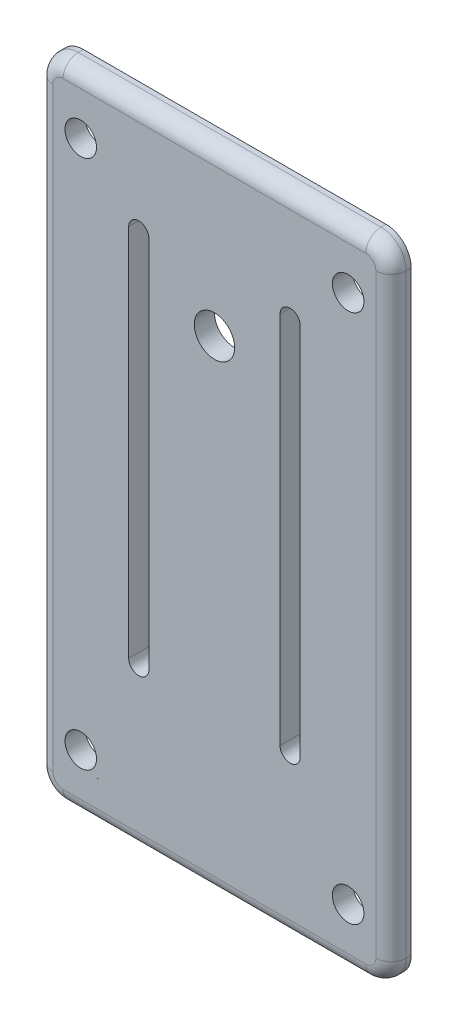
SolidWorks part; units mm, degrees
ref_plane "Front Plane" through (0, 0, 0) normal (0, 0, 1) x (1, 0, 0)
ref_plane "Top Plane" through (0, 0, 0) normal (0, 1, 0) x (1, 0, 0)
ref_plane "Right Plane" through (0, 0, 0) normal (1, 0, 0) x (0, 0, -1)
sketch "Sketch1" plane through (0, 0, 0) normal (0, 0, 1) x (1, 0, 0)
  line L1 (0, 32) -> (0, -32) construction
  line L2 (16.455, 32) -> (-16.455, 32) construction
  line L3 (-16.455, -32) -> (16.455, -32) construction
  line L4 (17.455, 31) -> (17.455, -31) construction
  line L5 (17.455, 0) -> (-17.455, 0) construction
  line L6 (-17.455, 31) -> (-17.455, -31) construction
  line L7 (17.7124, 32) -> (16.455, 32) construction
  line L8 (-15, -32) -> (15, -32)
  line L9 (-17.5, -29.5) -> (-17.5, 29.5)
  line L10 (-15, 32) -> (15, 32)
  line L11 (17.5, -29.5) -> (17.5, 29.5)
  line L12 (0, 32) -> (0, -32) construction
  line L13 (-17.5, 0) -> (17.5, 0) construction
  arc A0 (-15, -32) -> (-17.5, -29.5) centre (-15, -29.5) cw
  arc A1 (15, -32) -> (17.5, -29.5) centre (15, -29.5) ccw
  arc A2 (15, 32) -> (17.5, 29.5) centre (15, 29.5) cw
  arc A3 (-17.5, 29.5) -> (-15, 32) centre (-15, 29.5) cw
  circle A4 centre (-11.5563, -27.8796) radius 0.0197
  circle A5 centre (-13.25, -26.25) radius 1.5625
  circle A6 centre (-13.25, 26.25) radius 1.5625
  circle A7 centre (-13.25, -26.25) radius 2.37 construction
  circle A8 centre (13.25, -26.25) radius 1.5625
  circle A9 centre (13.25, 26.25) radius 1.5625
  point P12 (0, 0)
  point P25 (17.5, 32)
  point P32 (0, 0)
  dimension "D3" = 2.5
  dimension "D4" = 0.0393
  dimension "D5" = 3.125
  dimension "D1" = 35
  dimension "D2" = 64
  dimension "D6" = 11.5563
  dimension "D7" = 27.8796
extrude "Boss-Extrude1" add sketch "Sketch1" along normal blind 2
sketch "Sketch2" plane through (0, 0, 2) normal (0, 0, 1) x (1, 0, 0)
  line L0 (-13.6273, 22.1478) -> (-13.6273, -16.8522) construction
  line L1 (-11.75, 22.1478) -> (-15.5046, 22.1478) construction
  line L2 (-15.5046, -16.8522) -> (-11.75, -16.8522) construction
  line L4 (0, 2.52) -> (-13.6273, 2.52) construction
  line L6 (-7.5, -16) -> (-7.5, 21.04) construction
  line L9 (0, -16.85) -> (0, 21.89) construction
  line L12 (-8.5, -16) -> (-8.5, 21.04)
  line L15 (-6.5, -16) -> (-6.5, 21.04)
  line L16 (7.5, -16) -> (7.5, 21.04) construction
  line L17 (8.5, -16) -> (8.5, 21.04)
  line L18 (6.5, -16) -> (6.5, 21.04)
  line L19 (17.5, -29.5) -> (17.5, 29.5) construction
  line L20 (-15, -32) -> (15, -32) construction
  line L21 (-13.6273, 2.6478) -> (0, 2.6478) construction
  arc A4 (-8.5, -16) -> (-6.5, -16) centre (-7.5, -16) ccw
  arc A5 (-6.5, 21.04) -> (-8.5, 21.04) centre (-7.5, 21.04) ccw
  arc A6 (8.5, -16) -> (6.5, -16) centre (7.5, -16) cw
  arc A7 (6.5, 21.04) -> (8.5, 21.04) centre (7.5, 21.04) cw
  point P11 (7.5, 2.52)
  point P14 (-7.5, 2.52)
  dimension "D3" = 17.5
  dimension "D4" = 16
  dimension "D2" = 10
  dimension "D1" = 2
  dimension "D5" = 34.52
fillet "Fillet1" radius 1.5 8 edges at (-16.7678, -31.2678, 2) (0, -32, 2) (16.7678, -31.2678, 2) (16.7678, 31.2678, 2) (17.5, 0, 2) (-16.7678, 31.2678, 2) (-17.5, 0, 2) (0, 32, 2)
sketch "Sketch3" plane through (0, 0, 2) normal (0, 0, 1) x (1, 0, 0)
  line L0 (16, -29.5) -> (16, 29.5) construction
  line L6 (-8.88, 26.4) -> (8.88, 26.4) construction
  circle A0 centre (0, 15.9) radius 2
  dimension "D1" = 10.5
  dimension "D2" = 4
  dimension "D3" = 16
extrude "Cut-Extrude2" cut sketch "Sketch3" against normal through all contours A0
extrude "Cut-Extrude3" cut sketch "Sketch2" against normal through all
